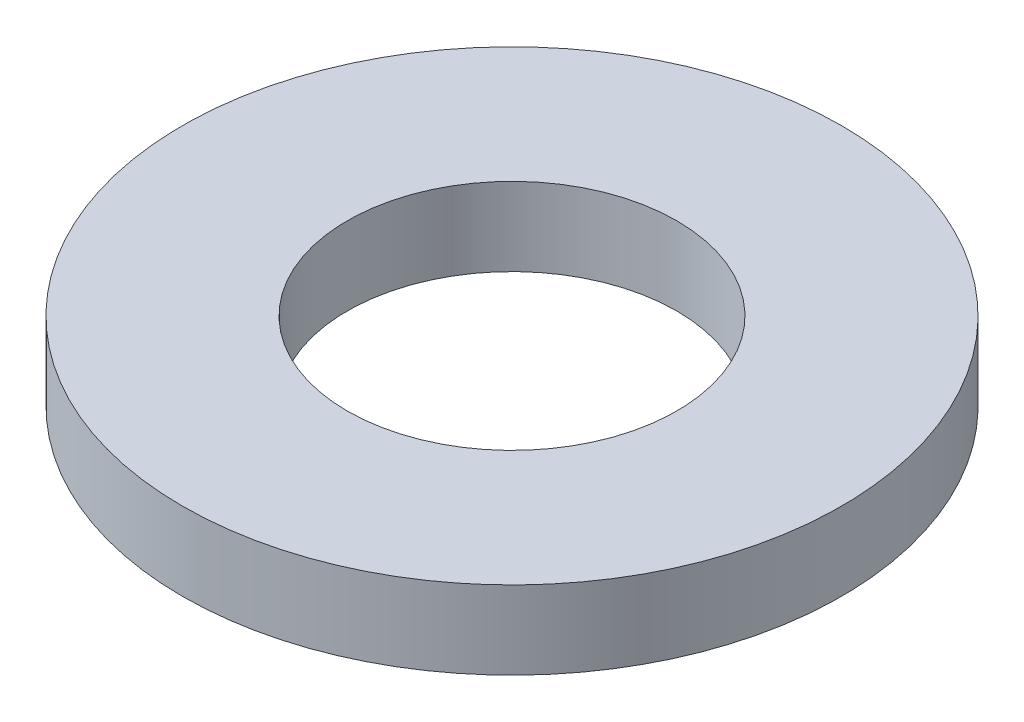
SolidWorks part; units mm, degrees
material "AISI 316 Stainless Steel Sheet (SS)"
ref_plane "Front Plane" through (0, 0, 0) normal (0, 0, 1) x (1, 0, 0)
ref_plane "Top Plane" through (0, 0, 0) normal (0, 1, 0) x (1, 0, 0)
ref_plane "Right Plane" through (0, 0, 0) normal (1, 0, 0) x (0, 0, -1)
sketch "Sketch1" plane through (0, 0, 0) normal (0, 1, 0) x (1, 0, 0)
  circle A0 centre (0, 0) radius 3.9624
  dimension "OD" = 7.9248
extrude "Boss-Extrude1" add sketch "Sketch1" along normal blind 0.9398
sketch "Sketch5" plane through (0, 0.9398, 0) normal (0, 1, 0) x (-1, 0, 0)
  circle A0 centre (0, 0) radius 1.9812
  dimension "ID" = 3.9624
extrude "Cut-Extrude1" cut sketch "Sketch5" against normal through all
